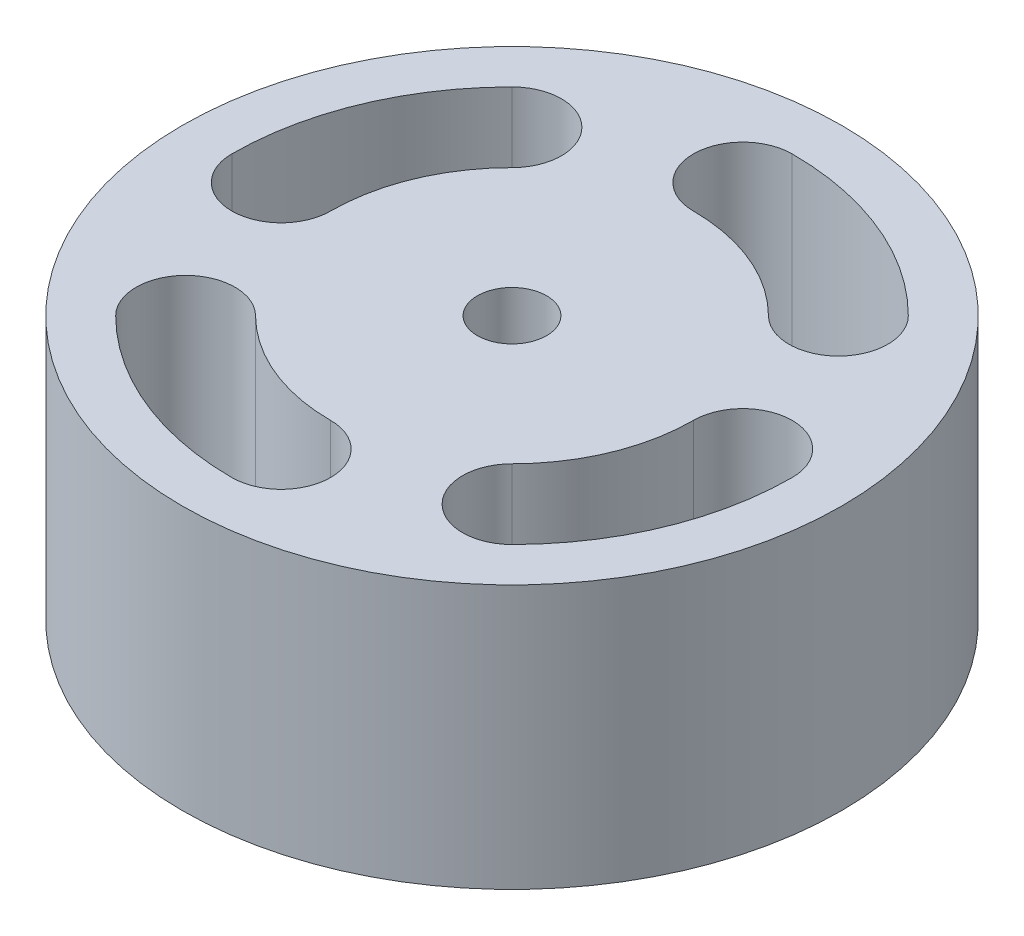
SolidWorks part; units mm, degrees
ref_plane "前视基准面" through (0, 0, 0) normal (0, 0, 1) x (1, 0, 0)
ref_plane "上视基准面" through (0, 0, 0) normal (0, 1, 0) x (1, 0, 0)
ref_plane "右视基准面" through (0, 0, 0) normal (1, 0, 0) x (0, 0, -1)
other "Configuration Table"
sketch "草图1" plane through (0, 0, 0) normal (0, 1, 0) x (1, 0, 0)
  circle A0 centre (0, 0) radius 50
  dimension "D1" = 100
extrude "凸台-拉伸1" add sketch "草图1" along normal blind 20
sketch "草图2" plane through (0, 20, 0) normal (0, 1, 0) x (1, 0, 0)
  circle A0 centre (0, 0) radius 5.25
  dimension "D1" = 10.5
extrude "切除-拉伸1" cut sketch "草图2" against normal blind 20
sketch "草图3" plane through (0, 20, 0) normal (0, 1, 0) x (1, 0, 0)
  line L0 (-1000, 0) -> (49000, 0) construction
  line L1 (0, -1000) -> (0, 49000) construction
  circle A0 centre (0, 0) radius 35
  circle A1 centre (0, 35) radius 7.5
  circle A2 centre (24.7487, 24.7487) radius 7.5
  circle A3 centre (35, 0) radius 7.5
  circle A4 centre (24.7487, -24.7487) radius 7.5
  circle A5 centre (0, -35) radius 7.5
  circle A6 centre (-24.7487, -24.7487) radius 7.5
  circle A7 centre (-35, 0) radius 7.5
  circle A8 centre (-24.7487, 24.7487) radius 7.5
  circle A9 centre (0, 0) radius 42.5
  circle A10 centre (0, 0) radius 27.5
  point P28 (0, 0)
  dimension "D1" = 70
  dimension "D2" = 15
  dimension "D3" = 8
extrude "切除-拉伸2" cut sketch "草图3" against normal blind 20 contours A10 A8 A0 A7 | A8 A9 A7 A0 | A0 A7 | A0 A7 | A0 A8 | A0 A8 | A0 A6 | A0 A6 | A6 A9 A5 A0 | A10 A6 A0 A5 | A0 A5 | A0 A5 | A0 A4 | A0 A4 | A4 A9 A3 A0 | A10 A4 A0 A3 | A0 A3 | A0 A3 | A0 A2 | A0 A2 | A10 A2 A0 A1 | A2 A9 A1 A0 | A0 A1 | A0 A1
sketch "草图4" plane through (0, 0, 0) normal (0, -1, 0) x (1, 0, 0)
  circle A0 centre (0, 0) radius 50
  circle A1 centre (0, 0) radius 5.25
  circle A2 centre (0, 0) radius 27.5
  circle A3 centre (0, 0) radius 42.5
  arc M1 (30.052, -30.052) -> (0, -42.5) centre (0, 0) cw
  arc M2 (0, -42.5) -> (0, -27.5) centre (0, -35) cw
  arc M3 (0, -27.5) -> (19.4454, -19.4454) centre (0, 0) ccw
  arc M4 (19.4454, -19.4454) -> (30.052, -30.052) centre (24.7487, -24.7487) cw
  arc M5 (30.052, 30.052) -> (42.5, 0) centre (0, 0) cw
  arc M6 (42.5, 0) -> (27.5, 0) centre (35, 0) cw
  arc M7 (27.5, 0) -> (19.4454, 19.4454) centre (0, 0) ccw
  arc M8 (19.4454, 19.4454) -> (30.052, 30.052) centre (24.7487, 24.7487) cw
  arc M9 (-19.4454, 19.4454) -> (-30.052, 30.052) centre (-24.7487, 24.7487) cw
  arc M10 (-30.052, 30.052) -> (0, 42.5) centre (0, 0) cw
  arc M11 (0, 42.5) -> (0, 27.5) centre (0, 35) cw
  arc M12 (0, 27.5) -> (-19.4454, 19.4454) centre (0, 0) ccw
  arc M13 (-19.4454, -19.4454) -> (-30.052, -30.052) centre (-24.7487, -24.7487) cw
  arc M14 (-30.052, -30.052) -> (-42.5, 0) centre (0, 0) cw
  arc M15 (-42.5, 0) -> (-27.5, 0) centre (-35, 0) cw
  arc M16 (-27.5, 0) -> (-19.4454, -19.4454) centre (0, 0) ccw
  circle M17 centre (0, 0) radius 5.25
  circle M18 centre (0, 0) radius 50
extrude "凸台-拉伸2" add sketch "草图4" along normal blind 20 contours A3 A2 M4 M6 | A2 M3 M7 M12 M16 M17 | A3 A2 M8 M11 | A3 A2 M9 M15 | A3 A2 M13 M2 | A3 M18 M1 M14 M10 M5
